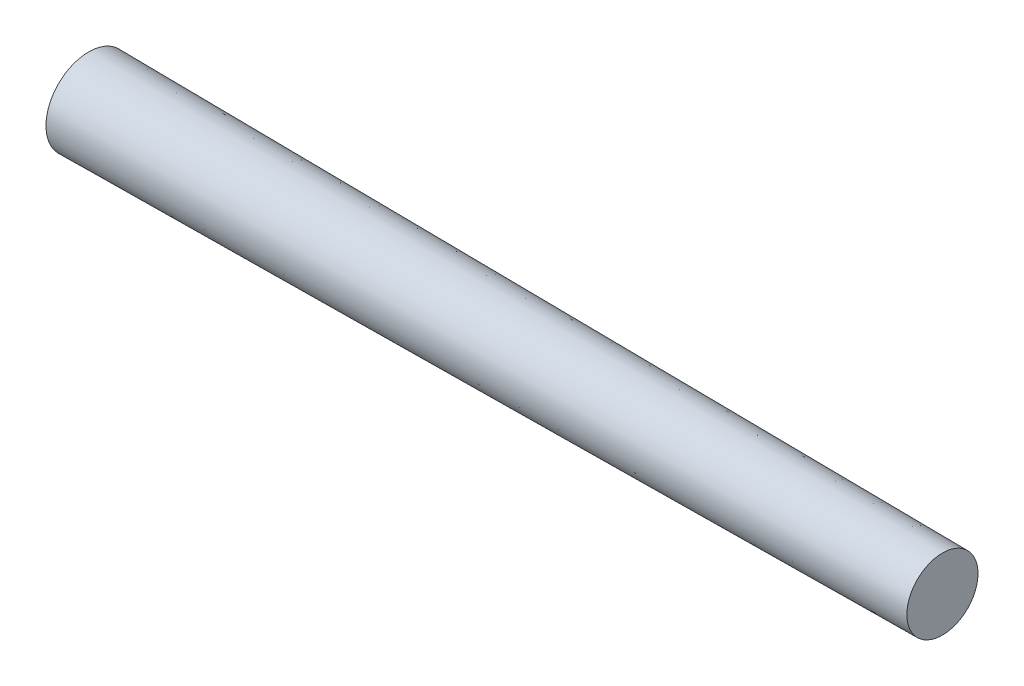
SolidWorks part; units mm, degrees
ref_plane "Front Plane" through (0, 0, 0) normal (0, 0, 1) x (1, 0, 0)
ref_plane "Top Plane" through (0, 0, 0) normal (0, 1, 0) x (1, 0, 0)
ref_plane "Right Plane" through (0, 0, 0) normal (1, 0, 0) x (0, 0, -1)
sketch "Sketch1" plane through (0, 0, 0) normal (0, 0, 1) x (1, 0, 0)
  line L0 (-16.2857, 0) -> (-16.2857, 3)
  line L1 (-16.2857, 3) -> (43.7143, 2.5)
  line L2 (43.7143, 2.5) -> (43.7143, 0)
  line L3 (43.7143, 0) -> (-16.2857, 0)
  dimension "D1" = 3
  dimension "D2" = 2.5
  dimension "D3" = 60
revolve "Revolve1" add sketch "Sketch1" angle 360 about L3
